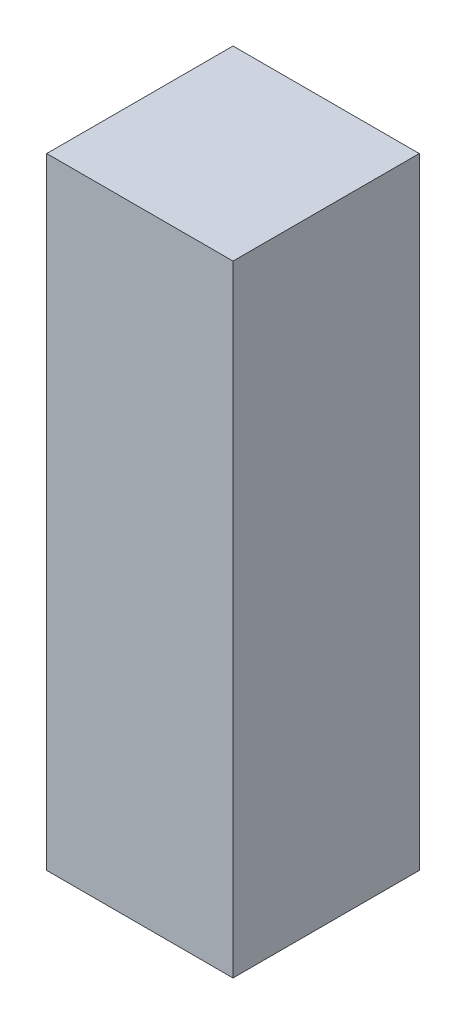
SolidWorks part; units mm, degrees
material "Pine"
ref_plane "Front Plane" through (0, 0, 0) normal (0, 0, 1) x (1, 0, 0)
ref_plane "Top Plane" through (0, 0, 0) normal (0, 1, 0) x (1, 0, 0)
ref_plane "Right Plane" through (0, 0, 0) normal (1, 0, 0) x (0, 0, -1)
sketch "Sketch1" plane through (0, 0, 0) normal (0, 1, 0) x (1, 0, 0)
  line L1 (-19.05, -19.05) -> (19.05, -19.05)
  line L2 (-19.05, -19.05) -> (-19.05, 19.05)
  line L3 (-19.05, 19.05) -> (19.05, 19.05)
  line L4 (19.05, -19.05) -> (19.05, 19.05)
  line L5 (-19.05, -19.05) -> (19.05, 19.05) construction
  line L6 (-19.05, 19.05) -> (19.05, -19.05) construction
  point P0 (0, 0)
  dimension "D1" = 38.1
  dimension "D2" = 38.1
extrude "Boss-Extrude1" add sketch "Sketch1" along normal blind 127
